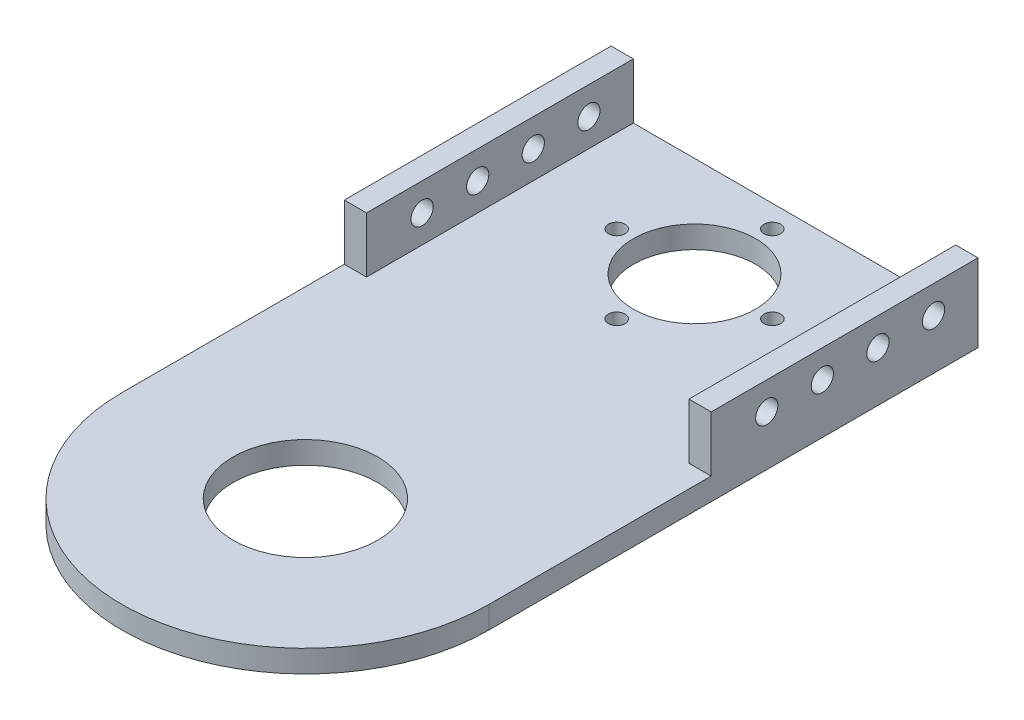
SolidWorks part; units mm, degrees
material "6061 合金"
ref_plane "前视基准面" through (0, 0, 0) normal (0, 0, 1) x (1, 0, 0)
ref_plane "上视基准面" through (0, 0, 0) normal (0, 1, 0) x (1, 0, 0)
ref_plane "右视基准面" through (0, 0, 0) normal (1, 0, 0) x (0, 0, -1)
sketch "草图1" plane through (0, 0, 0) normal (0, 0, 1) x (1, 0, 0)
  line L0 (0, 47.6325) -> (0, -53.9266) construction
  line L1 (33, 0) -> (-33, 0)
  line L2 (-33, 0) -> (-33, 14)
  line L3 (-33, 14) -> (-29, 14)
  line L4 (-29, 14) -> (-29, 4)
  line L5 (-29, 4) -> (29, 4)
  line L7 (29, 14) -> (29, 4)
  line L8 (33, 14) -> (29, 14)
  line L9 (33, 0) -> (33, 14)
  point P10 (0, 4)
  point P11 (0, 0)
extrude "凸台-拉伸1" add sketch "草图1" along normal mid plane 60
sketch "草图2" plane through (33, 0, 0) normal (1, 0, 0) x (0, 0, -1)
  line L0 (-30, 0) -> (-30, 9) construction
  line L1 (-30, 0) -> (-30, 14) construction
  line L2 (0, 19.6652) -> (0, -8.571) construction
  line L4 (-30, 9) -> (-20, 9) construction
  line L5 (-20, 9) -> (-10, 9) construction
  circle A4 centre (-20, 9) radius 2
  circle A5 centre (-10, 9) radius 2
  circle A6 centre (10, 9) radius 2
  circle A8 centre (0, 9) radius 2
  dimension "D2" = 10
  dimension "D1" = 9
  dimension "D3" = 10
  dimension "D4" = 20
extrude "切除-拉伸1" cut sketch "草图2" against normal up to surface (66 mm away) up to face at (-33, 7, 0)
sketch "草图3" plane through (0, 4, 0) normal (0, 1, 0) x (1, 0, 0)
  circle A0 centre (0, 0) radius 11
  circle A1 centre (0, 0) radius 14 construction
  circle A2 centre (0, 14) radius 1.5
  circle A3 centre (14, 0) radius 1.5
  circle A4 centre (0, -14) radius 1.5
  circle A5 centre (-14, 0) radius 1.5
  point P15 (0, 0)
  dimension "D1" = 4
extrude "切除-拉伸2" cut sketch "草图3" against normal up to surface (4 mm away) up to face at (0, 0, 0)
sketch "草图4" plane through (0, 0, 0) normal (0, -1, 0) x (1, 0, 0)
  line L0 (0, 0) -> (0, 70) construction
  line L1 (-33, 30) -> (33, 30) construction
  line L2 (-33, 30) -> (33, 30)
  line L5 (-33, 70) -> (-33, 30)
  line L6 (33, 70) -> (33, 30)
  circle A0 centre (0, 70) radius 13
  circle A1 centre (0, 70) radius 12.5 construction
  arc A7 (33, 70) -> (-33, 70) centre (0, 70) ccw
  point P16 (0, 55)
extrude "凸台-拉伸2" add sketch "草图4" against normal up to surface (4 mm away) up to face at (0, 4, -12.5)
sketch "草图5" plane through (33, 0, 0) normal (1, 0, 0) x (0, 0, -1)
  line L0 (-30, 14) -> (18, 14) construction
  line L1 (-30, 14) -> (30, 14) construction
  line L2 (18, 14) -> (18, 0)
  line L3 (-70, 0) -> (30, 0) construction
  line L4 (18, 14) -> (30, 14)
  line L5 (30, 14) -> (30, 0)
  line L6 (30, 0) -> (18, 0)
extrude "切除-拉伸3" cut sketch "草图5" against normal up to surface (66 mm away) up to face at (-33, 9, 18)
